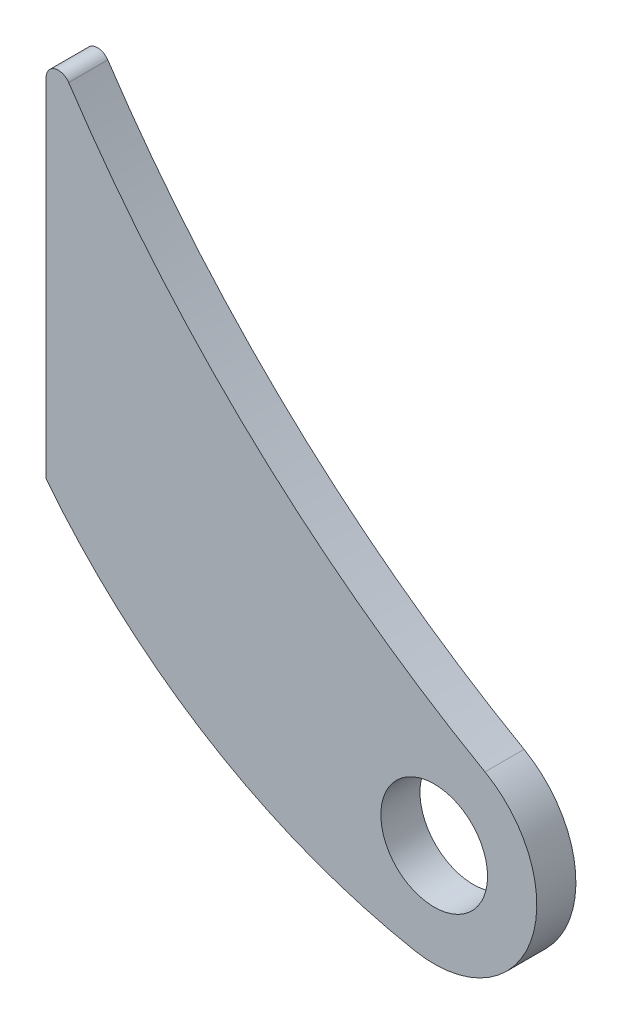
SolidWorks part; units mm, degrees
ref_plane "Alzado" through (0, 0, 0) normal (0, 0, 1) x (1, 0, 0)
ref_plane "Planta" through (0, 0, 0) normal (0, 1, 0) x (1, 0, 0)
ref_plane "Vista lateral" through (0, 0, 0) normal (1, 0, 0) x (0, 0, -1)
sketch "Croquis1" plane through (0, 0, 0) normal (0, 0, 1) x (1, 0, 0)
  line L7 (-44.5526, 70.0702) -> (-44.5526, -24.9298)
  circle A0 centre (50, -55) radius 13
  circle A3 centre (0, 0) radius 13 construction
  arc A6 (-44.5526, 70.0702) -> (62.3767, -33.2786) centre (210.8965, 227.3779) ccw
  arc A7 (-44.5526, -24.9298) -> (45.3298, -79.5599) centre (73.351, 67.7996) ccw
  arc A8 (45.3298, -79.5599) -> (62.3767, -33.2786) centre (50, -55) ccw
  dimension "D1" = 26
  dimension "D5" = 94.5526
  dimension "D6" = 300
  dimension "D7" = 150
  dimension "D9" = 55
  dimension "D10" = 50
  dimension "D11" = 26
  dimension "D8" = 50
  dimension "D2" = 44.5526
  dimension "D3" = 70.0702
  dimension "D4" = 95
extrude "Saliente-Extruir1" add sketch "Croquis1" along normal mid plane 9.53
fillet "Redondeo2" radius 3 1 edges at (-44.5526, 70.0702, 0)
